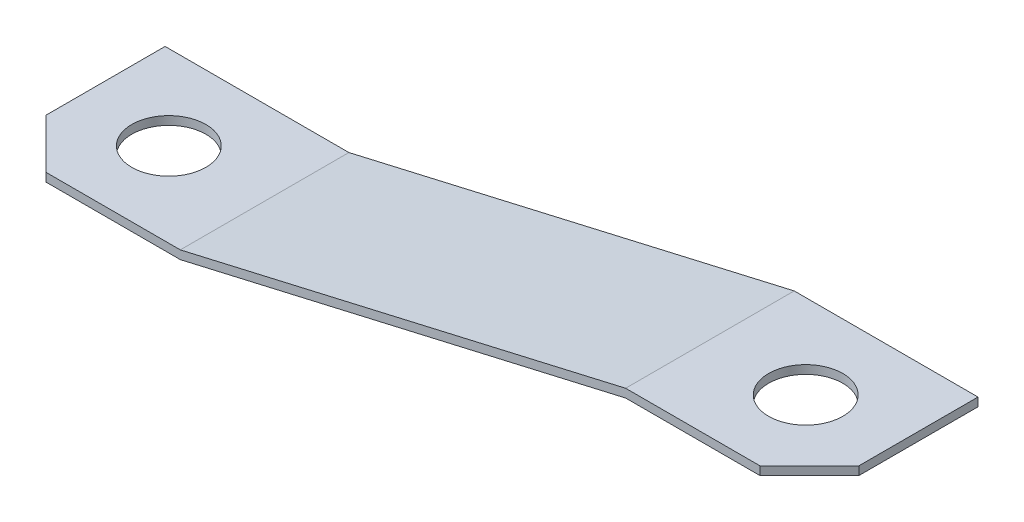
SolidWorks part; units mm, degrees
ref_plane "Plano frontal" through (0, 0, 0) normal (0, 0, 1) x (1, 0, 0)
ref_plane "Plano superior" through (0, 0, 0) normal (0, 1, 0) x (1, 0, 0)
ref_plane "Plano direito" through (0, 0, 0) normal (1, 0, 0) x (0, 0, -1)
sketch "Esboço1" plane through (0, 0, 0) normal (0, 0, 1) x (1, 0, 0)
  line L0 (-57.3649, 0) -> (-31.3649, 0)
  line L1 (-31.3649, 0) -> (31.6351, 14.5447)
  line L2 (31.6351, 14.5447) -> (57.6351, 14.5447)
  line L3 (57.6351, 14.5447) -> (57.6351, 13.3447)
  line L4 (57.6351, 13.3447) -> (31.6351, 13.3447)
  line L5 (31.6351, 13.3447) -> (-31.3649, -1.2)
  line L6 (-31.3649, -1.2) -> (-57.3649, -1.2)
  line L7 (-57.3649, -1.2) -> (-57.3649, 0)
  dimension "D1" = 167
  dimension "D2" = 1.2
  dimension "D3" = 26
  dimension "D4" = 26
  dimension "D5" = 26
  dimension "D6" = 115
  dimension "D7" = 26
extrude "Ressalto-extrusão1" add sketch "Esboço1" along normal blind 23.85
chamfer "Chanfro1" distance 7 angle 45 2 edges at (-57.3649, -0.6, 23.85) (57.6351, 13.9447, 23.85)
sketch "Esboço2" plane through (0, 0, 0) normal (0, 1, 0) x (1, 0, 0)
  line L0 (0.1351, -23.85) -> (0.1351, -45.3257) construction
  line L2 (-31.3649, -11.925) -> (-49.1352, -11.925) construction
  line L3 (-31.3649, -23.85) -> (-31.3649, 0) construction
  line L4 (-44.9149, -8.425) -> (-44.9149, -11.925) construction
  line L5 (31.6351, -23.85) -> (-31.3649, -23.85) construction
  circle A0 centre (-44.9149, -11.925) radius 5.25
  circle A1 centre (45.1851, -11.925) radius 5.25
extrude "Corte-extrusão1" cut sketch "Esboço2" against normal through all and the other way through all
